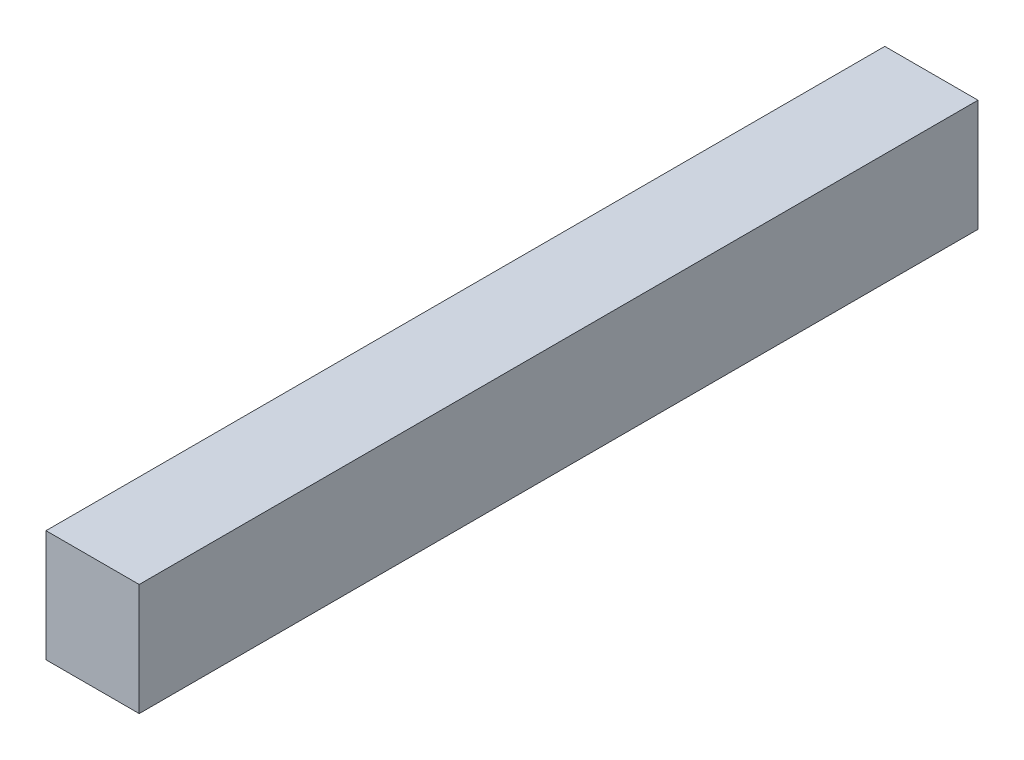
SolidWorks part; units mm, degrees
material "Plain Carbon Steel"
ref_plane "Front Plane" through (0, 0, 0) normal (0, 0, 1) x (1, 0, 0)
ref_plane "Top Plane" through (0, 0, 0) normal (0, 1, 0) x (1, 0, 0)
ref_plane "Right Plane" through (0, 0, 0) normal (1, 0, 0) x (0, 0, -1)
sketch "Sketch1" plane through (0, 0, 0) normal (0, 1, 0) x (1, 0, 0)
  line L1 (-12.5, -112.5) -> (12.5, -112.5)
  line L2 (-12.5, -112.5) -> (-12.5, 112.5)
  line L3 (-12.5, 112.5) -> (12.5, 112.5)
  line L4 (12.5, -112.5) -> (12.5, 112.5)
  line L5 (-12.5, -112.5) -> (12.5, 112.5) construction
  line L6 (-12.5, 112.5) -> (12.5, -112.5) construction
  point P0 (0, 0)
  dimension "D1" = 225
  dimension "D2" = 25
extrude "Boss-Extrude1" add sketch "Sketch1" against normal blind 30
